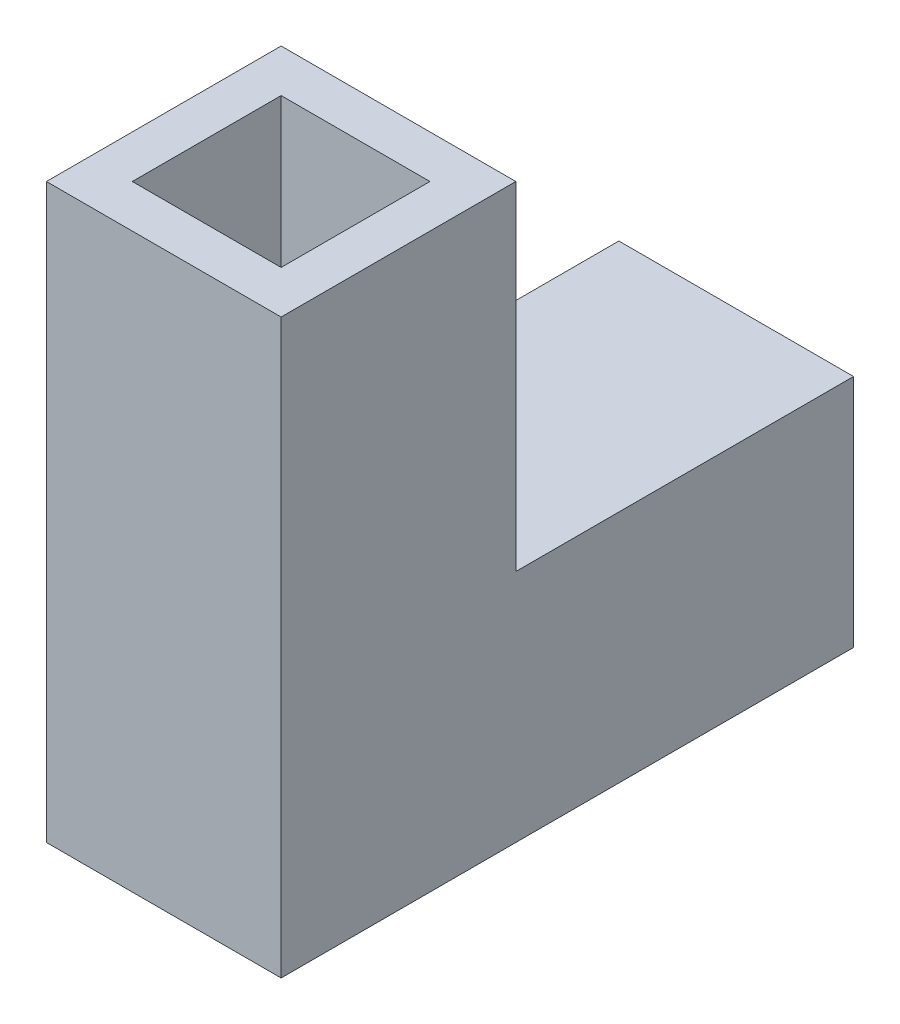
SolidWorks part; units mm, degrees
material "Ti-6Al-4VSolution treated and aged (SS)"
ref_plane "Front Plane" through (0, 0, 0) normal (0, 0, 1) x (1, 0, 0)
ref_plane "Top Plane" through (0, 0, 0) normal (0, 1, 0) x (1, 0, 0)
ref_plane "Right Plane" through (0, 0, 0) normal (1, 0, 0) x (0, 0, -1)
sketch "Sketch1" plane through (0, 0, 0) normal (0, 1, 0) x (1, 0, 0)
  line L1 (-2.6, 2.6) -> (2.6, 2.6)
  line L2 (-2.6, 2.6) -> (-2.6, -2.6)
  line L3 (-2.6, -2.6) -> (2.6, -2.6)
  line L4 (2.6, 2.6) -> (2.6, -2.6)
  line L5 (-2.6, 2.6) -> (2.6, -2.6) construction
  line L6 (-2.6, -2.6) -> (2.6, 2.6) construction
  line L7 (-4.1, 4.1) -> (4.1, 4.1)
  line L8 (-4.1, 4.1) -> (-4.1, -4.1)
  line L9 (-4.1, -4.1) -> (4.1, -4.1)
  line L10 (4.1, 4.1) -> (4.1, -4.1)
  line L11 (-4.1, 4.1) -> (4.1, -4.1) construction
  line L12 (-4.1, -4.1) -> (4.1, 4.1) construction
  point P0 (0, 0)
  point P6 (0, 0)
  dimension "D1" = 5.2
  dimension "D2" = 1.5
extrude "Boss-Extrude1" add sketch "Sketch1" along normal blind 20 contours L10 L7 L8 L9 L1 L4 L3 L2 | L4 L1 L2 L3
sketch "Sketch2" plane through (0, 0, 4.1) normal (0, 0, -1) x (-1, 0, 0)
  line L0 (4.1, 20) -> (4.1, 0) construction
  line L1 (-4.1, 0) -> (4.1, 0)
  line L2 (-4.1, 0) -> (-4.1, 8.2)
  line L3 (-4.1, 8.2) -> (4.1, 8.2)
  line L4 (4.1, 0) -> (4.1, 8.2)
  line L5 (-2.6, 1.5) -> (-2.6, 6.7)
  line L6 (-2.6, 6.7) -> (2.6, 6.7)
  line L7 (2.6, 1.5) -> (2.6, 6.7)
  line L8 (-2.6, 1.5) -> (2.6, 1.5)
  line M14 (4.1, 0) -> (-4.1, 0)
  line M15 (-4.1, 0) -> (-4.1, 20)
  line M17 (4.1, 20) -> (4.1, 0)
  dimension "D2" = 5.2
  dimension "D1" = 1.5
extrude "Boss-Extrude2" add sketch "Sketch2" along normal blind 20 contours L8 L5 L6 L7 | L3 L5 L8 L7 L6 M15 M17 M14
shell "Shell1" thickness 1.5
